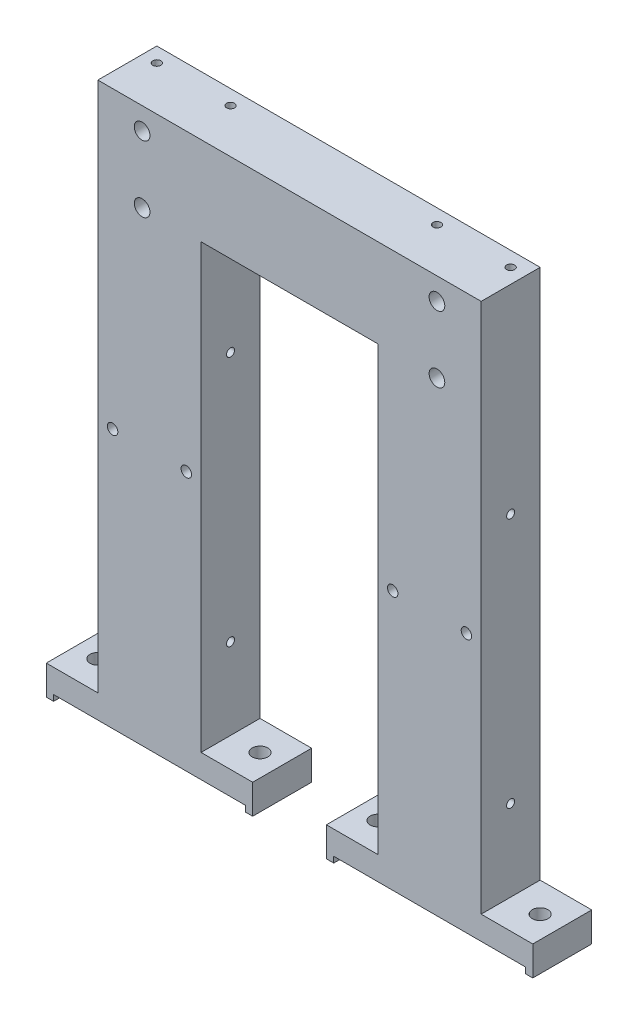
SolidWorks part; units mm, degrees
material "6061 Alloy"
ref_plane "Front Plane" through (0, 0, 0) normal (0, 0, 1) x (1, 0, 0)
ref_plane "Top Plane" through (0, 0, 0) normal (0, 1, 0) x (1, 0, 0)
ref_plane "Right Plane" through (0, 0, 0) normal (1, 0, 0) x (0, 0, -1)
sketch "Sketch1" plane through (0, 0, 0) normal (0, 0, 1) x (1, 0, 0)
  line L1 (-82.55, -120.65) -> (82.55, -120.65)
  line L2 (-82.55, -120.65) -> (-82.55, 120.65)
  line L3 (-82.55, 120.65) -> (82.55, 120.65)
  line L4 (82.55, -120.65) -> (82.55, 120.65)
  line L5 (-82.55, -120.65) -> (82.55, 120.65) construction
  line L6 (-82.55, 120.65) -> (82.55, -120.65) construction
  point P0 (0, 0)
  dimension "D1" = 241.3
  dimension "D2" = 165.1
extrude "Boss-Extrude1" add sketch "Sketch1" along normal blind 25.4
sketch "Sketch2" plane through (0, 0, 25.4) normal (0, 0, 1) x (1, 0, 0)
  line L0 (-82.55, -120.65) -> (82.55, -120.65) construction
  line L1 (-38.1, -120.65) -> (38.1, -120.65)
  line L2 (-38.1, -120.65) -> (-38.1, 82.55)
  line L3 (-38.1, 82.55) -> (38.1, 82.55)
  line L4 (38.1, -120.65) -> (38.1, 82.55)
  line L5 (-82.55, 120.65) -> (-82.55, -120.65) construction
  line L6 (82.55, 120.65) -> (-82.55, 120.65) construction
  dimension "D1" = 203.2
  dimension "D2" = 76.2
  dimension "D3" = 44.45
  dimension "D4" = 38.1
extrude "Cut-Extrude1" cut sketch "Sketch2" against normal through all
sketch "Sketch7" plane through (0, 0, 25.4) normal (0, 0, 1) x (1, 0, 0)
  line L0 (-82.55, -120.65) -> (-38.1, -120.65) construction
  line L1 (-104.775, -107.95) -> (-15.875, -107.95)
  line L2 (-104.775, -107.95) -> (-104.775, -120.65)
  line L3 (-104.775, -120.65) -> (-15.875, -120.65)
  line L4 (-15.875, -107.95) -> (-15.875, -120.65)
  line L5 (-104.775, -107.95) -> (-15.875, -120.65) construction
  line L6 (-104.775, -120.65) -> (-15.875, -107.95) construction
  line L7 (-82.55, 120.65) -> (-82.55, -120.65) construction
  point P0 (-60.325, -114.3)
  dimension "D1" = 0
  dimension "D2" = 88.9
  dimension "D3" = 22.225
  dimension "D4" = 12.7
extrude "Boss-Extrude4" add sketch "Sketch7" against normal blind 25.4
sketch "Sketch8" plane through (0, -120.65, 0) normal (0, -1, 0) x (-1, 0, 0)
  line L0 (104.775, -25.4) -> (15.875, -25.4) construction
  line L1 (101.6, 0) -> (19.05, 0)
  line L2 (101.6, 0) -> (101.6, -25.4)
  line L3 (101.6, -25.4) -> (19.05, -25.4)
  line L4 (19.05, 0) -> (19.05, -25.4)
  line L5 (101.6, 0) -> (19.05, -25.4) construction
  line L6 (101.6, -25.4) -> (19.05, 0) construction
  line L8 (104.775, 0) -> (104.775, -25.4) construction
  line L9 (15.875, 0) -> (15.875, -25.4) construction
  point P0 (60.325, -12.7)
  dimension "D1" = 25.4
  dimension "D2" = 3.175
  dimension "D3" = 3.175
extrude "Cut-Extrude4" cut sketch "Sketch8" against normal blind 2.54
mirror "Mirror3" about plane through (0, 0, 0) normal (1, 0, 0) of "Cut-Extrude4", "Boss-Extrude4"
hole_wizard "1/4 Clearance Hole1" positions "Sketch12" profile "Sketch13" hole size "1/4" standard "ANSI Inch"
sketch "Sketch12" plane through (0, -107.95, 0) normal (0, 1, 0) x (1, 0, 0)
  line L0 (-104.775, 0) -> (-104.775, -25.4) construction
  line L1 (-82.55, 0) -> (-104.775, 0) construction
  line L2 (-15.875, 0) -> (-38.1, 0) construction
  line L3 (-15.875, 0) -> (-15.875, -25.4) construction
  line L4 (15.875, 0) -> (15.875, -25.4) construction
  line L5 (15.875, 0) -> (38.1, 0) construction
  line L6 (82.55, 0) -> (104.775, 0) construction
  line L7 (104.775, 0) -> (104.775, -25.4) construction
  point P0 (-95.25, -12.7)
  point P2 (-25.4, -12.7)
  point P4 (25.4, -12.7)
  point P6 (95.25, -12.7)
  dimension "D1" = 9.525
  dimension "D2" = 12.7
  dimension "D3" = 12.7
  dimension "D4" = 9.525
  dimension "D5" = 9.525
  dimension "D6" = 12.7
  dimension "D7" = 12.7
  dimension "D8" = 9.525
sketch "Sketch13" plane through (-95.25, -107.95, 12.7) normal (1, 0, 0) x (0, 0, 1)
  line L0 (0, 0) -> (0, 10.16)
  line L1 (0, 10.16) -> (3.3782, 10.16)
  line L2 (3.3782, 10.16) -> (3.3782, 0)
  line L5 (3.3782, 0) -> (0, 0)
  line L11 (0, -6.35) -> (0, 107.95) construction
  dimension "Thru Hole Dia." = 6.7564
  dimension "Thru Hole Depth" = 10.16
hole_wizard "CBORE for 1/4 Socket Head Cap Screw1" positions "Sketch20" profile "Sketch21" counterbore size "1/4" standard "ANSI Inch" end condition through all
sketch "Sketch20" plane through (0, 0, 0) normal (0, 0, -1) x (-1, 0, 0)
  line L0 (-82.55, 120.65) -> (82.55, 120.65) construction
  line L1 (-82.55, -107.95) -> (-82.55, 120.65) construction
  line L2 (82.55, 120.65) -> (82.55, -107.95) construction
  point P0 (-63.5, 111.125)
  point P2 (-63.5, 82.55)
  point P4 (63.5, 111.125)
  point P6 (63.5, 82.55)
  dimension "D1" = 9.525
  dimension "D2" = 28.575
  dimension "D3" = 9.525
  dimension "D4" = 28.575
  dimension "D5" = 19.05
  dimension "D6" = 19.05
  dimension "D7" = 19.05
  dimension "D8" = 19.05
sketch "Sketch21" plane through (63.5, 111.125, 0) normal (1, 0, 0) x (0, 1, 0)
  line L0 (0, 0) -> (0, 25.4)
  line L1 (0, 25.4) -> (3.3782, 25.4)
  line L3 (3.3782, 25.4) -> (3.3782, 6.35)
  line L4 (3.3782, 6.35) -> (5.5562, 6.35)
  line L5 (5.5562, 6.35) -> (5.5562, 0)
  line L7 (5.5562, 0) -> (0, 0)
  line L11 (0, -6.35) -> (0, 107.95) construction
  dimension "Thru Hole Dia." = 6.7564
  dimension "Thru Hole Depth" = 25.4
  dimension "C'Bore Dia." = 11.1125
  dimension "C'Bore Depth" = 6.35
hole_wizard "#8-32 Tapped Hole1" positions "Sketch22" profile "Sketch23" tap size "#8-32" standard "ANSI Inch"
sketch "Sketch22" plane through (0, 120.65, 0) normal (0, 1, 0) x (1, 0, 0)
  line L0 (-82.55, -25.4) -> (-82.55, 0) construction
  line L1 (82.55, -25.4) -> (82.55, 0) construction
  line L2 (82.55, -25.4) -> (-82.55, -25.4) construction
  point P0 (-76.2, -6.35)
  point P2 (-44.45, -6.35)
  point P4 (44.45, -6.35)
  point P6 (76.2, -6.35)
  dimension "D1" = 6.35
  dimension "D2" = 38.1
  dimension "D3" = 38.1
  dimension "D4" = 6.35
  dimension "D5" = 19.05
  dimension "D6" = 19.05
  dimension "D7" = 19.05
  dimension "D8" = 19.05
cosmetic thread "Hole Thread1" parameters "D1"=8.382, "D2"=4.1656
cosmetic thread "Hole Thread2" parameters "D1"=8.382, "D2"=4.1656
cosmetic thread "Hole Thread3" parameters "D1"=8.382, "D2"=4.1656
cosmetic thread "Hole Thread4" parameters "D1"=8.382, "D2"=4.1656
sketch "Sketch23" plane through (-76.2, 120.65, 6.35) normal (1, 0, 0) x (0, 0, 1)
  line L0 (0, 0) -> (0, 13.7378)
  line L1 (0, 13.7378) -> (1.7272, 12.7)
  line L2 (1.7272, 12.7) -> (1.7272, 0)
  line L5 (1.7272, 0) -> (0, 0)
  line L10 (0, 13.7378) -> (-1.7272, 12.7) construction
  line L11 (0, -6.35) -> (0, 107.95) construction
  dimension "Tap Drill Dia." = 3.4544
  dimension "Tap Drill Depth" = 12.7
  dimension "Drill Angle" = 118
hole_wizard "CBORE for #8 Socket Head Cap Screw1" positions "Sketch24" profile "Sketch25" counterbore size "#8" standard "ANSI Inch" end condition through all
sketch "Sketch24" plane through (0, 0, 0) normal (0, 0, -1) x (-1, 0, 0)
  line L0 (-82.55, 120.65) -> (82.55, 120.65) construction
  line L1 (-82.55, -107.95) -> (-82.55, 120.65) construction
  line L2 (38.1, 82.55) -> (38.1, -107.95) construction
  line L3 (82.55, 120.65) -> (82.55, -107.95) construction
  point P0 (-76.2, -6.35)
  point P2 (-44.45, -6.35)
  point P4 (44.45, -6.35)
  point P6 (76.2, -6.35)
  dimension "D1" = 127
  dimension "D2" = 127
  dimension "D3" = 127
  dimension "D4" = 127
  dimension "D5" = 6.35
  dimension "D6" = 31.75
  dimension "D7" = 6.35
  dimension "D8" = 6.35
sketch "Sketch25" plane through (76.2, -6.35, 0) normal (1, 0, 0) x (0, 1, 0)
  line L0 (0, 0) -> (0, 25.4)
  line L1 (0, 25.4) -> (2.2479, 25.4)
  line L3 (2.2479, 25.4) -> (2.2479, 4.1656)
  line L4 (2.2479, 4.1656) -> (3.9687, 4.1656)
  line L5 (3.9687, 4.1656) -> (3.9687, 0)
  line L7 (3.9687, 0) -> (0, 0)
  line L11 (0, -6.35) -> (0, 107.95) construction
  dimension "Thru Hole Dia." = 4.4958
  dimension "Thru Hole Depth" = 25.4
  dimension "C'Bore Dia." = 7.9375
  dimension "C'Bore Depth" = 4.1656
hole_wizard "#8-32 Tapped Hole2" positions "Sketch26" profile "Sketch27" tap size "#8-32" standard "ANSI Inch"
sketch "Sketch26" plane through (-82.55, 0, 0) normal (-1, 0, 0) x (0, 0, 1)
  line L0 (25.4, 120.65) -> (25.4, -107.95) construction
  line L1 (0, -120.65) -> (25.4, -120.65) construction
  point P0 (12.7, -73.025)
  point P2 (12.7, 34.925)
  dimension "D1" = 12.7
  dimension "D2" = 12.7
  dimension "D3" = 107.95
  dimension "D4" = 47.625
sketch "Sketch27" plane through (-82.55, -73.025, 12.7) normal (0, 1, 0) x (0, 0, 1)
  line L0 (0, 0) -> (0, 44.45)
  line L1 (0, 44.45) -> (1.7272, 44.45)
  line L2 (1.7272, 44.45) -> (1.7272, 0)
  line L5 (1.7272, 0) -> (0, 0)
  line L11 (0, -6.35) -> (0, 107.95) construction
  dimension "Thru Tap Drill Dia." = 3.4544
  dimension "Thru Tap Drill Depth" = 44.45
cosmetic thread "Hole Thread5" parameters "D2"=4.1656
cosmetic thread "Hole Thread6" parameters "D2"=4.1656
mirror "Mirror4" about plane through (0, 0, 0) normal (1, 0, 0) of "#8-32 Tapped Hole2"
